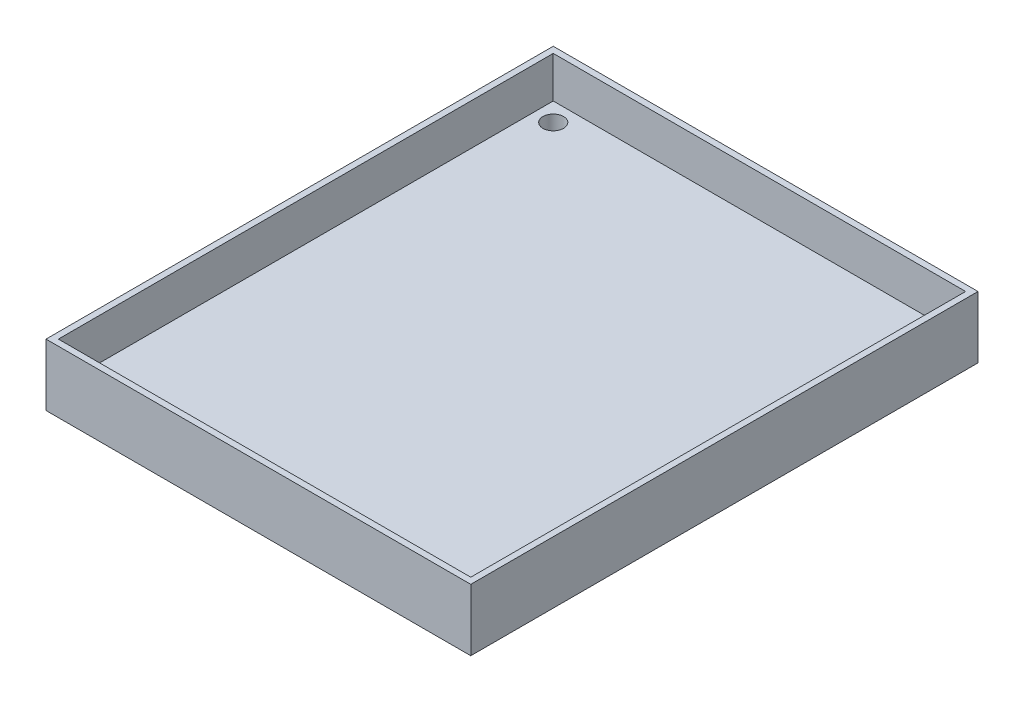
SolidWorks part; units mm, degrees
ref_plane "Front Plane" through (0, 0, 0) normal (0, 0, 1) x (1, 0, 0)
ref_plane "Top Plane" through (0, 0, 0) normal (0, 1, 0) x (1, 0, 0)
ref_plane "Right Plane" through (0, 0, 0) normal (1, 0, 0) x (0, 0, -1)
sketch "Sketch1" plane through (0, 0, 0) normal (0, 1, 0) x (1, 0, 0)
  line L1 (-103, 123) -> (103, 123)
  line L2 (-103, 123) -> (-103, -123)
  line L3 (-103, -123) -> (103, -123)
  line L4 (103, 123) -> (103, -123)
  line L5 (-103, 123) -> (103, -123) construction
  line L6 (-103, -123) -> (103, 123) construction
  point P0 (0, 0)
  dimension "D1" = 246
  dimension "D2" = 206
extrude "Boss-Extrude1" add sketch "Sketch1" along normal blind 60
sketch "Sketch2" plane through (0, 60, 0) normal (0, 1, 0) x (1, 0, 0)
  line L0 (103, 123) -> (-103, 123) construction
  line L1 (-100, 120) -> (100, 120)
  line L2 (-100, 120) -> (-100, -120)
  line L3 (-100, -120) -> (100, -120)
  line L4 (100, 120) -> (100, -120)
  line L5 (-100, 120) -> (100, -120) construction
  line L6 (-100, -120) -> (100, 120) construction
  line L7 (103, -123) -> (103, 123) construction
  point P0 (0, 0)
  dimension "D1" = 3
  dimension "D2" = 3
extrude "Cut-Extrude1" cut sketch "Sketch2" against normal blind 50
sketch "Sketch3" plane through (0, 0, 0) normal (0, -1, 0) x (1, 0, 0)
  line L0 (-103, 123) -> (103, 123) construction
  line L1 (-91, 111) -> (91, 111)
  line L2 (-91, 111) -> (-91, -111)
  line L3 (-91, -111) -> (91, -111)
  line L4 (91, 111) -> (91, -111)
  line L5 (-91, 111) -> (91, -111) construction
  line L6 (-91, -111) -> (91, 111) construction
  line L7 (103, 123) -> (103, -123) construction
  circle A0 centre (91, 111) radius 5
  circle A1 centre (91, -111) radius 5
  circle A2 centre (-91, -111) radius 5
  circle A3 centre (-91, 111) radius 5
  point P0 (0, 0)
  dimension "D3" = 10
  dimension "D1" = 12
  dimension "D2" = 12
extrude "Cut-Extrude3" cut sketch "Sketch3" against normal through all contours L2 A3 L1 | L1 A3 L2 | L4 A0 L1 | L1 A0 L4 | L3 A1 L4 | L4 A1 L3 | L2 A2 L3 | L3 A2 L2
sketch "Sketch5" plane through (0, 60, 0) normal (0, 1, 0) x (1, 0, 0)
  line L1 (-103, 123) -> (103, 123)
  line L2 (-103, 123) -> (-103, -123)
  line L3 (-103, -123) -> (103, -123)
  line L4 (103, 123) -> (103, -123)
extrude "Cut-Extrude4" cut sketch "Sketch5" against normal blind 30
sketch "Sketch6" plane through (0, 0, 0) normal (0, -1, 0) x (1, 0, 0)
  line L1 (-65, 30) -> (65, 30)
  line L2 (-65, 30) -> (-65, -30)
  line L3 (-65, -30) -> (65, -30)
  line L4 (65, 30) -> (65, -30)
  line L5 (-65, 30) -> (65, -30) construction
  line L6 (-65, -30) -> (65, 30) construction
  point P0 (0, 0)
  dimension "D1" = 130
  dimension "D2" = 60
extrude "Cut-Extrude5" cut sketch "Sketch6" against normal blind 5
